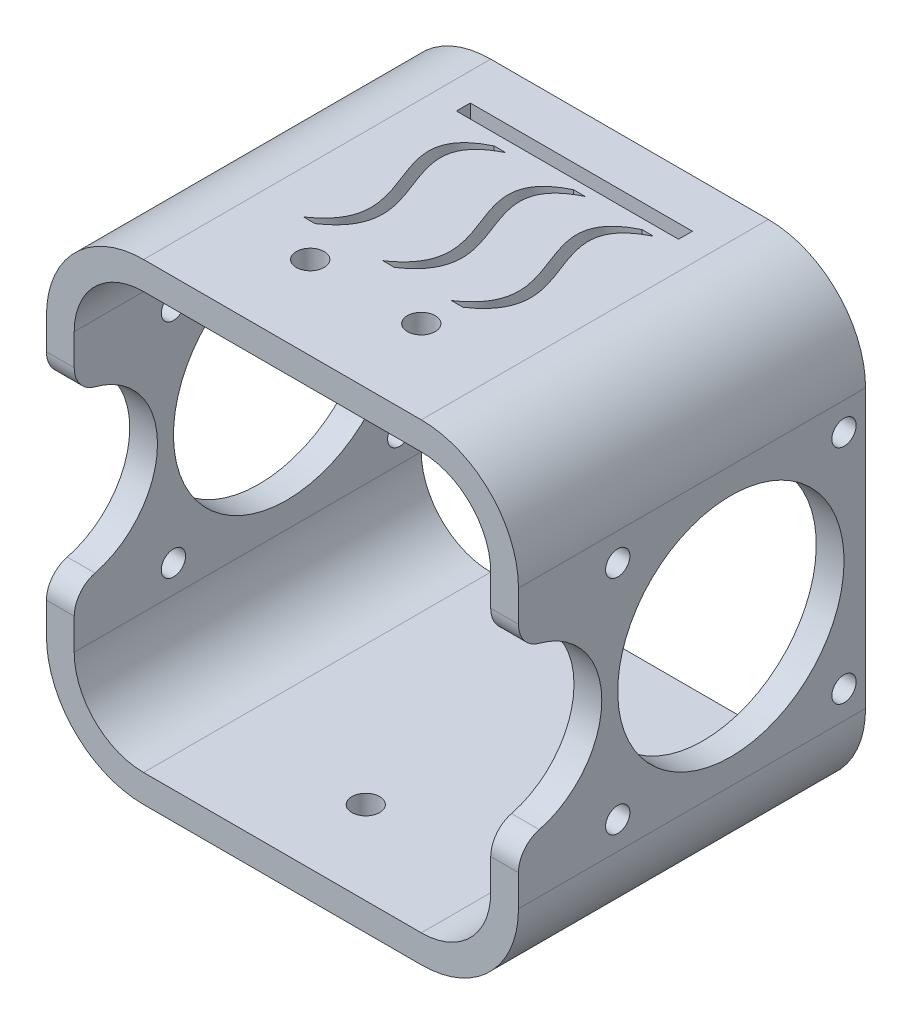
SolidWorks part; units mm, degrees
ref_plane "Piano frontale" through (0, 0, 0) normal (0, 0, 1) x (1, 0, 0)
ref_plane "Piano superiore" through (0, 0, 0) normal (0, 1, 0) x (1, 0, 0)
ref_plane "Piano destro" through (0, 0, 0) normal (1, 0, 0) x (0, 0, -1)
sketch "Schizzo1" plane through (0, 0, 0) normal (0, 0, 1) x (1, 0, 0)
  line L0 (-10, 0) -> (-50, 0)
  line L1 (0, -10) -> (0, -50)
  line L2 (-60, -10) -> (-60, -50)
  line L3 (-50, -60) -> (-10, -60)
  arc A0 (0, -50) -> (-10, -60) centre (-10, -50) cw
  arc A1 (-50, -60) -> (-60, -50) centre (-50, -50) cw
  arc A2 (0, -10) -> (-10, 0) centre (-10, -10) ccw
  arc A3 (-60, -10) -> (-50, 0) centre (-50, -10) cw
  point P7 (0, -60)
  point P10 (-60, -60)
  point P13 (0, 0)
  point P16 (-60, 0)
  dimension "D4" = 10
  dimension "D1" = 60
  dimension "D2" = 60
  dimension "D3" = 60
extrude "Estrusione-Sottile1" add sketch "Schizzo1" along normal blind 50 thin
sketch "Schizzo2" plane through (0, 4, 0) normal (0, 1, 0) x (1, 0, 0)
  line L0 (-30, 0) -> (-30, -50) construction
  line L1 (-10, 0) -> (-50, 0) construction
  line L2 (-10, -50) -> (-50, -50) construction
  circle A0 centre (-38, -38) radius 2
  circle A1 centre (-22, -38) radius 2
  dimension "D5" = 4
  dimension "D6" = 4
  dimension "D1" = 8
  dimension "D2" = 8
  dimension "D3" = 12
  dimension "D4" = 12
extrude "Taglio-Estrusione1" cut sketch "Schizzo2" against normal blind 10
sketch "Schizzo3" plane through (-64, 0, 0) normal (-1, 0, 0) x (0, 0, 1)
  line L0 (50, -10) -> (50, -50) construction
  circle A0 centre (50, -30) radius 12
  dimension "D1" = 24
extrude "Taglio-Estrusione2" cut sketch "Schizzo3" along direction (-1, 0, 0) on the side against the normal up to surface (68 mm away)
fillet "Raccordo1" radius 4 1 edges at (-62, -18, 50)
fillet "Raccordo2" radius 4 1 edges at (-62, -42, 50)
fillet "Raccordo3" radius 4 1 edges at (2, -18, 50)
fillet "Raccordo4" radius 4 1 edges at (2, -42, 50)
sketch "Schizzo4" plane through (0, -64, 0) normal (0, -1, 0) x (1, 0, 0)
  line L0 (-30, 50) -> (-30, 0) construction
  line L1 (-50, 50) -> (-10, 50) construction
  line L2 (-50, 0) -> (-10, 0) construction
  circle A0 centre (-30, 38) radius 2
  dimension "D1" = 4
  dimension "D2" = 12
extrude "Taglio-Estrusione3" cut sketch "Schizzo4" against normal blind 10
sketch "Schizzo5" plane through (0, 4, 0) normal (0, 1, 0) x (1, 0, 0)
  line L0 (-30, 0) -> (-30, -50) construction
  line L1 (-46, -6.9458) -> (-14, -6.9458)
  line L2 (-46, -6.9458) -> (-46, -8.9458)
  line L3 (-46, -8.9458) -> (-14, -8.9458)
  line L4 (-14, -6.9458) -> (-14, -8.9458)
  line L5 (-10, 0) -> (-50, 0) construction
  line L6 (-10, -50) -> (-50, -50) construction
  line L7 (-30.9605, -32.9287) -> (-32.6391, -32.9195)
  line L8 (-26.0641, -10.3322) -> (-27.7428, -10.3231)
  line L9 (-42.1357, -33.1817) -> (-43.8144, -33.1725)
  line L10 (-37.2394, -10.5852) -> (-38.918, -10.576)
  line L11 (-21.0473, -32.9631) -> (-22.7259, -32.9539)
  line L12 (-16.1509, -10.3666) -> (-17.8296, -10.3574)
  spline S0 degree 3 poles (-16.1509, -10.3666) (-27.5731, -15.9557) (-10.2901, -25.7029) (-21.0473, -32.9631) knots 0 0 0 0 1 1 1 1
  spline S1 degree 3 poles (-17.8296, -10.3574) (-29.2518, -15.9465) (-11.9688, -25.6937) (-22.7259, -32.9539) knots 0 0 0 0 1 1 1 1
  spline S2 degree 3 poles (-26.0641, -10.3322) (-37.4863, -15.9213) (-20.2033, -25.6686) (-30.9605, -32.9287) knots 0 0 0 0 1 1 1 1
  spline S3 degree 3 poles (-27.7428, -10.3231) (-39.1649, -15.9122) (-21.882, -25.6594) (-32.6391, -32.9195) knots 0 0 0 0 1 1 1 1
  spline S4 degree 3 poles (-37.2394, -10.5852) (-48.6615, -16.1743) (-31.3786, -25.9215) (-42.1357, -33.1817) knots 0 0 0 0 1 1 1 1
  spline S5 degree 3 poles (-38.918, -10.576) (-50.3402, -16.1651) (-33.0573, -25.9123) (-43.8144, -33.1725) knots 0 0 0 0 1 1 1 1
  dimension "D1" = 16
  dimension "D2" = 16
  dimension "D3" = 2
extrude "Taglio-Estrusione4" cut sketch "Schizzo5" against normal blind 10
sketch "Schizzo8" plane through (-64, 0, 0) normal (-1, 0, 0) x (0, 0, 1)
  circle A0 centre (19.4016, -30.0409) radius 16.3
extrude "Taglio-Estrusione6" cut sketch "Schizzo8" against normal up to surface (68 mm away) up to face at (4, -30, 35.7906)
sketch "Schizzo7" plane through (-64, 0, 0) normal (-1, 0, 0) x (0, 0, 1)
  line L0 (0, -30) -> (38, -30) construction
  line L1 (0, -10) -> (0, -50) construction
  line L2 (0, -14) -> (49.9676, -14) construction
  line L3 (0, -46) -> (49.9676, -46) construction
  line L4 (19.4016, -30.0409) -> (19.4016, -6.503) construction
  arc A0 (47, -18.381) -> (47, -41.619) centre (50, -30) ccw construction
  arc A1 (47, -18.381) -> (50, -14.5081) centre (46, -14.5081) ccw construction
  arc A2 (50, -45.4919) -> (47, -41.619) centre (46, -45.4919) ccw construction
  circle A3 centre (35.7016, -14) radius 1.75
  circle A4 centre (35.7016, -46) radius 1.75
  circle A5 centre (3.1016, -46) radius 1.75
  circle A6 centre (3.1016, -14) radius 1.75
  dimension "D4" = 3.5
  dimension "D1" = 16
  dimension "D2" = 16
extrude "Taglio-Estrusione5" cut sketch "Schizzo7" against normal up to surface (68 mm away) up to face at (4, -46.3409, 19.4016)
